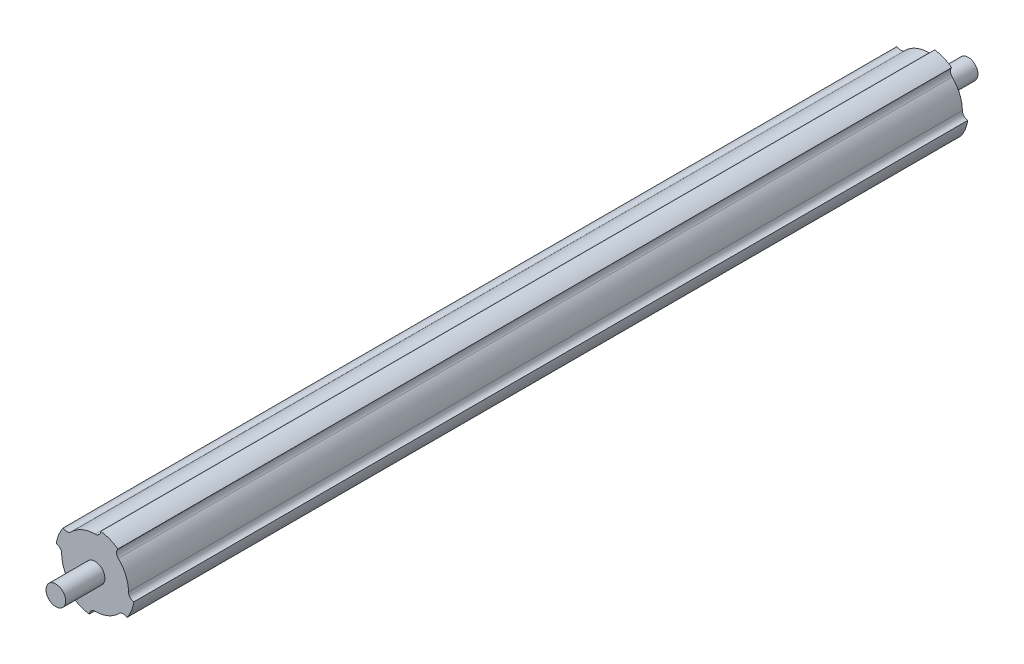
SolidWorks part; units mm, degrees
material "Rubber"
ref_plane "Front Plane" through (0, 0, 0) normal (0, 0, 1) x (1, 0, 0)
ref_plane "Top Plane" through (0, 0, 0) normal (0, 1, 0) x (1, 0, 0)
ref_plane "Right Plane" through (0, 0, 0) normal (1, 0, 0) x (0, 0, -1)
sketch "Sketch1" plane through (0, 0, 0) normal (0, 0, 1) x (1, 0, 0)
  circle A0 centre (0, 0) radius 25.4
extrude "Boss-Extrude1" add sketch "Sketch1" along normal blind 590.55 contours A0
sketch "Sketch2" plane through (0, 0, 0) normal (0, 0, 1) x (1, 0, 0)
  circle A0 centre (0, 0) radius 6.3619
extrude "Cut-Extrude1" cut sketch "Sketch2" along normal blind 25.4 flip side to cut contours A0
sketch "Sketch5" plane through (0, 0, 590.55) normal (0, 0, 1) x (1, 0, 0)
  circle A0 centre (0, 0) radius 6.3779
extrude "Cut-Extrude4" cut sketch "Sketch5" against normal blind 25.4 flip side to cut
sketch "Sketch6" plane through (0, 0, 0) normal (0, 0, 1) x (1, 0, 0)
  arc A0 (17.6602, 18.2559) -> (25.4, 0) centre (0, 0) cw construction
  circle A1 centre (0, 0) radius 25.4 construction
  arc A2 (29.1644, 0) -> (20.2775, 20.9615) centre (0, 0) ccw
  arc A3 (21.6356, 0) -> (15.0429, 15.5503) centre (0, 0) ccw
  arc A4 (21.6356, 0) -> (29.1644, 0) centre (25.4, 0) ccw
  arc A5 (20.2775, 20.9615) -> (15.0429, 15.5503) centre (17.6602, 18.2559) ccw
  point P6 (23.3851, 9.9144)
extrude "Cut-Extrude5" cut sketch "Sketch6" along normal blind 568.96
pattern_circular "CirPattern1" count 4 over 360 about axis through (0, 0, 0) along (0, 0, 1) of "Cut-Extrude5"
